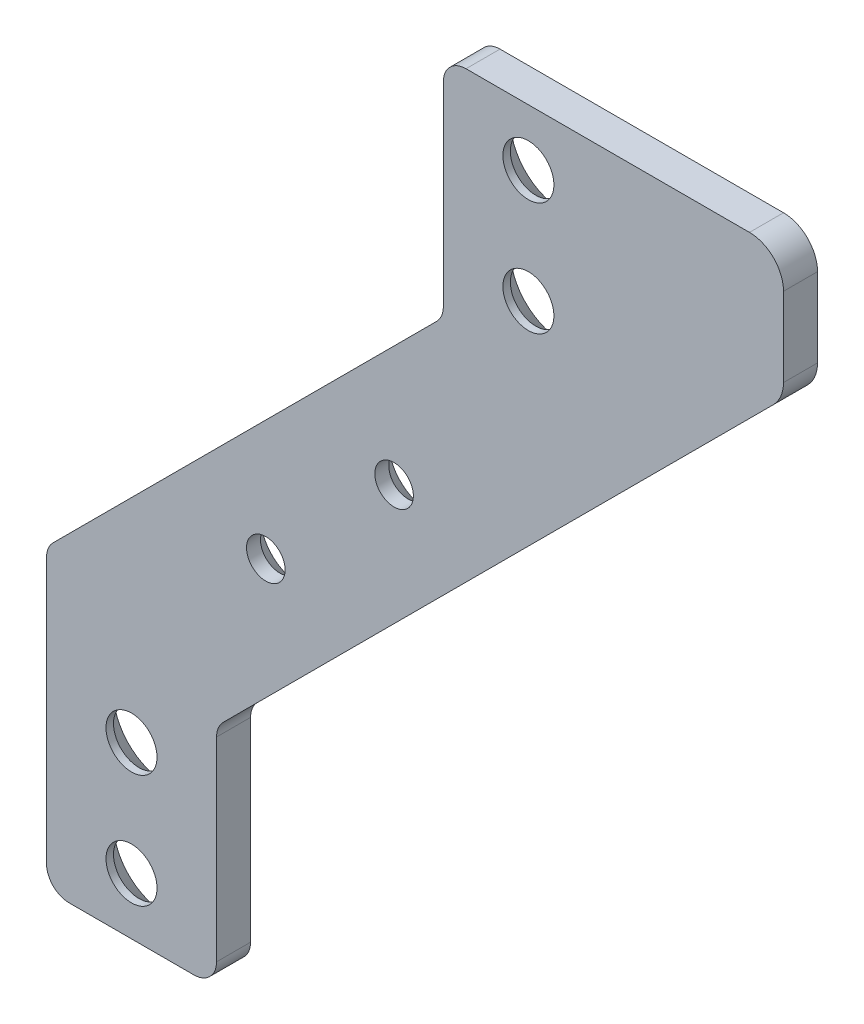
SolidWorks part; units mm, degrees
material "Thornel Mat VMA"
ref_plane "前视基准面" through (0, 0, 0) normal (0, 0, 1) x (1, 0, 0)
ref_plane "上视基准面" through (0, 0, 0) normal (0, 1, 0) x (1, 0, 0)
ref_plane "右视基准面" through (0, 0, 0) normal (1, 0, 0) x (0, 0, -1)
sketch "草图1" plane through (0, 0, 0) normal (0, 0, 1) x (1, 0, 0)
  line L0 (0, 0) -> (-15, 0)
  line L1 (-15, 0) -> (-15, 26.2132)
  line L2 (-15, 26.2132) -> (20, 61.2132)
  line L3 (20, 61.2132) -> (20, 81.2132)
  line L4 (20, 81.2132) -> (35, 81.2132)
  line L5 (35, 81.2132) -> (35, 55)
  line L6 (35, 55) -> (0, 20)
  line L7 (0, 20) -> (0, 0)
  line L8 (-95, 88.5038) -> (-95, -84.3524) construction
  line L9 (-7.5, 15) -> (-7.5, 0) construction
  line L10 (27.5, 81.2132) -> (27.5, 55.9789) construction
  circle A0 centre (-7.5, 15) radius 2 construction
  circle A1 centre (-7.5, 5) radius 2 construction
  circle A2 centre (27.5, 76.2132) radius 2 construction
  circle A3 centre (27.5, 66.2132) radius 2 construction
  point P22 (27.5, 66.2132)
  point P23 (-7.5, 5)
  point P24 (-7.5, 15)
  point P26 (27.5, 76.2132)
  dimension "D7" = 4
  dimension "D8" = 4
  dimension "D9" = 10
  dimension "D10" = 5
  dimension "D13" = 4
  dimension "D14" = 4
  dimension "D15" = 10
  dimension "D16" = 5
  dimension "D1" = 260
  dimension "D2" = 190
  dimension "D3" = 45
  dimension "D4" = 15
  dimension "D5" = 15
  dimension "D6" = 15
  dimension "D11" = 20
  dimension "D12" = 20
extrude "凸台-拉伸1" add sketch "草图1" along normal blind 3
fillet "圆角1" radius 2 8 edges at (0, 0, 1.5) (-15, 0, 1.5) (-15, 26.2132, 1.5) (20, 61.2132, 1.5) (20, 81.2132, 1.5) (35, 55, 1.5) (0, 20, 1.5) (35, 81.2132, 1.5)
hole_wizard "M4 六角凹锥坑头螺钉的锥形沉头孔1" positions "3D草图1" profile "草图2" countersink size "M4" standard "DIN"
sketch3d "3D草图1"
  point P3 (27.5, 76.2132, 0)
  point P5 (27.5, 66.2132, 0)
  point P7 (-7.5, 15, 0)
  point P9 (-7.5, 5, 0)
sketch "草图2" plane through (27.5, 76.2132, 0) normal (1, 0, 0) x (0, 1, 0)
  line L0 (0, 0) -> (0, 25.8519)
  line L1 (0, 25.8519) -> (2.25, 24.5)
  line L2 (2.25, 24.5) -> (2.25, 2.34)
  line L3 (2.25, 2.34) -> (4.59, 0)
  line L5 (4.59, 0) -> (0, 0)
  line L6 (-2.25, 2.34) -> (-4.59, 0) construction
  line L10 (0, 25.8519) -> (-2.25, 24.5) construction
  line L11 (0, -6.35) -> (0, 107.95) construction
  dimension "孔直径" = 4.5
  dimension "孔深度" = 24.5
  dimension "近端锥形沉头孔直径" = 9.18
  dimension "近端锥形沉头孔角度" = 90
  dimension "导头角度" = 118
sketch "草图3" plane through (0, 0, 0) normal (0, 0, -1) x (-1, 0, 0)
  line L0 (-0.5858, 20.5858) -> (10.0208, 31.1924) construction
  line L1 (-19.4142, 60.6274) -> (14.4142, 26.799) construction
  line L2 (-19.4142, 60.6274) -> (-30.0208, 50.0208) construction
  line L3 (-0.5858, 20.5858) -> (-34.4142, 54.4142) construction
  line L4 (-24.7175, 55.3241) -> (4.7175, 25.8891) construction
  point P10 (-10, 40.6066)
  point P13 (-15.6569, 46.2635)
  point P14 (-4.3431, 34.9497)
  dimension "D1" = 8
  dimension "D2" = 8
hole_wizard "M3 六角凹锥坑头螺钉的锥形沉头孔1" positions "3D草图2" profile "草图4" countersink size "M3" standard "DIN"
sketch3d "3D草图2"
  point P0 (15.6569, 46.2635, 0)
  point P4 (4.3431, 34.9497, 0)
sketch "草图4" plane through (15.6569, 46.2635, 0) normal (1, 0, 0) x (0, 1, 0)
  line L0 (0, 0) -> (0, 25.5215)
  line L1 (0, 25.5215) -> (1.7, 24.5)
  line L2 (1.7, 24.5) -> (1.7, 1.77)
  line L3 (1.7, 1.77) -> (3.47, 0)
  line L5 (3.47, 0) -> (0, 0)
  line L6 (-1.7, 1.77) -> (-3.47, 0) construction
  line L10 (0, 25.5215) -> (-1.7, 24.5) construction
  line L11 (0, -6.35) -> (0, 107.95) construction
  dimension "孔直径" = 3.4
  dimension "孔深度" = 24.5
  dimension "近端锥形沉头孔直径" = 6.94
  dimension "近端锥形沉头孔角度" = 90
  dimension "导头角度" = 118
sketch "草图5" plane through (0, 0, 0) normal (0, 0, -1) x (-1, 0, 0)
  line L0 (-33, 81.2132) -> (-50, 81.2132)
  line L1 (-50, 81.2132) -> (-50, 70)
  line L2 (-50, 70) -> (-34.4142, 54.4142)
  line L3 (-35, 55.8284) -> (-35, 79.2132) construction
  line L4 (-35, 55.8284) -> (-35, 79.2132)
  arc A0 (-35, 55.8284) -> (-34.4142, 54.4142) centre (-33, 55.8284) ccw construction
  arc A1 (-33, 81.2132) -> (-35, 79.2132) centre (-33, 79.2132) ccw construction
  arc A2 (-35, 55.8284) -> (-34.4142, 54.4142) centre (-33, 55.8284) ccw
  arc A3 (-33, 81.2132) -> (-35, 79.2132) centre (-33, 79.2132) ccw
  dimension "D1" = 45
  dimension "D2" = 15
extrude "凸台-拉伸2" add sketch "草图5" against normal up to surface (3 mm away) up to face at (13.9569, 46.2635, 3)
fillet "圆角2" radius 3 2 edges at (50, 70, 1.5) (50, 81.2132, 1.5)
